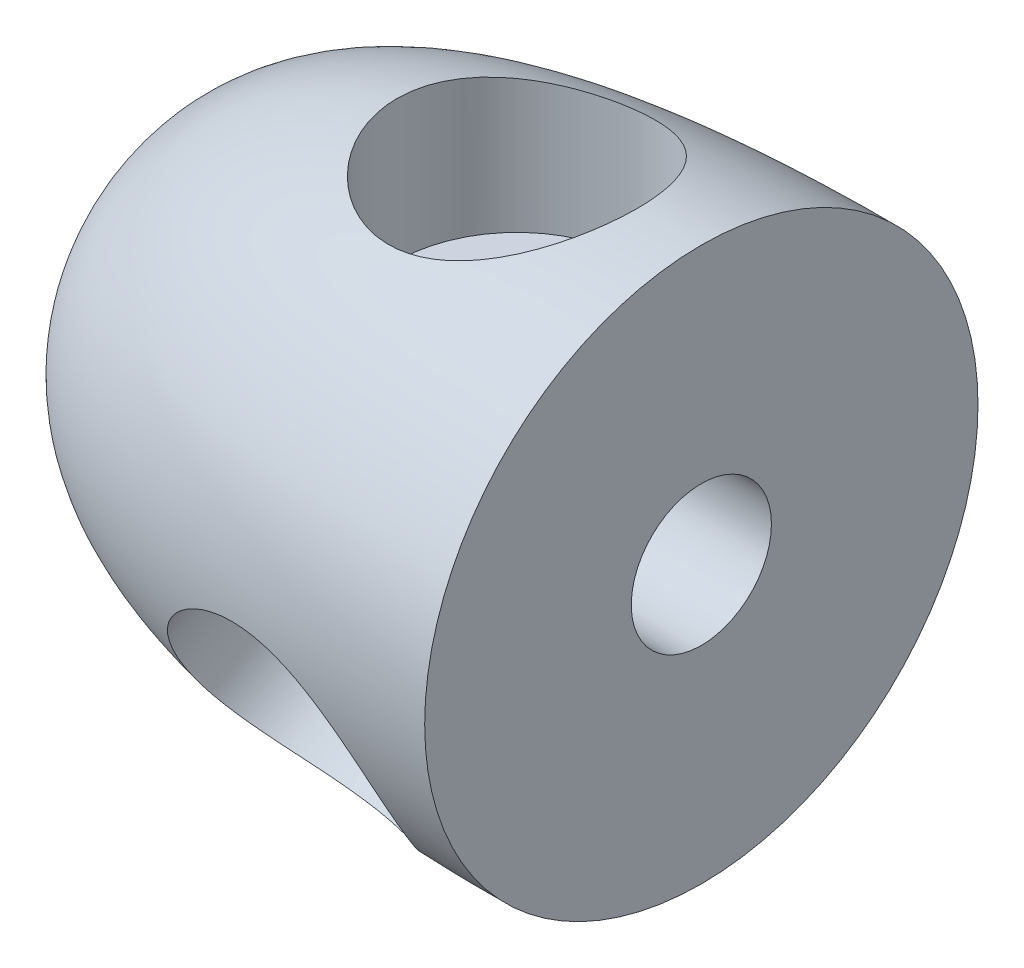
SolidWorks part; units mm, degrees
ref_plane "Front Plane" through (0, 0, 0) normal (0, 0, 1) x (1, 0, 0)
ref_plane "Top Plane" through (0, 0, 0) normal (0, 1, 0) x (1, 0, 0)
ref_plane "Right Plane" through (0, 0, 0) normal (1, 0, 0) x (0, 0, -1)
sketch "Sketch1" plane through (0, 0, 0) normal (0, 0, 1) x (1, 0, 0)
  line L0 (0, 0) -> (0, 19.05)
  line L1 (-38.1, 0) -> (0, 0)
  line L2 (-38.1, 0) -> (-38.1, 19.05) construction
  line L3 (-38.1, 19.05) -> (0, 19.05) construction
  spline S0 degree 3 poles (-38.1, 0) (-38.1, 14.199) (-25.4442, 19.05) (0, 19.05) knots 0 0 0 0 1 1 1 1
  dimension "D1" = 38.1
  dimension "D2" = 19.05
revolve "Revolve1" add sketch "Sketch1" angle 360 about L1
ref_plane "Plane1" through (0, 19.05, 0) normal (0, 1, 0) x (1, 0, 0)
sketch "Sketch2" plane through (0, 19.05, 0) normal (0, 1, 0) x (1, 0, 0)
  circle A0 centre (-12.7, 0) radius 8.255
  point P2 (0, 0)
  dimension "D1" = 16.51
  dimension "D2" = 12.7
extrude "Cut-Extrude1" cut sketch "Sketch2" against normal blind 11.43 contours A0
pattern_circular "CirPattern3" count 3 over 360 about axis through (0, 0, 0) along (1, 0, 0) of "Cut-Extrude1"
sketch "Sketch3" plane through (0, 0, 0) normal (1, 0, 0) x (0, 0, -1)
  circle A0 centre (0, 0) radius 4.826
  dimension "D1" = 9.652
extrude "Cut-Extrude2" cut sketch "Sketch3" against normal blind 12.7
